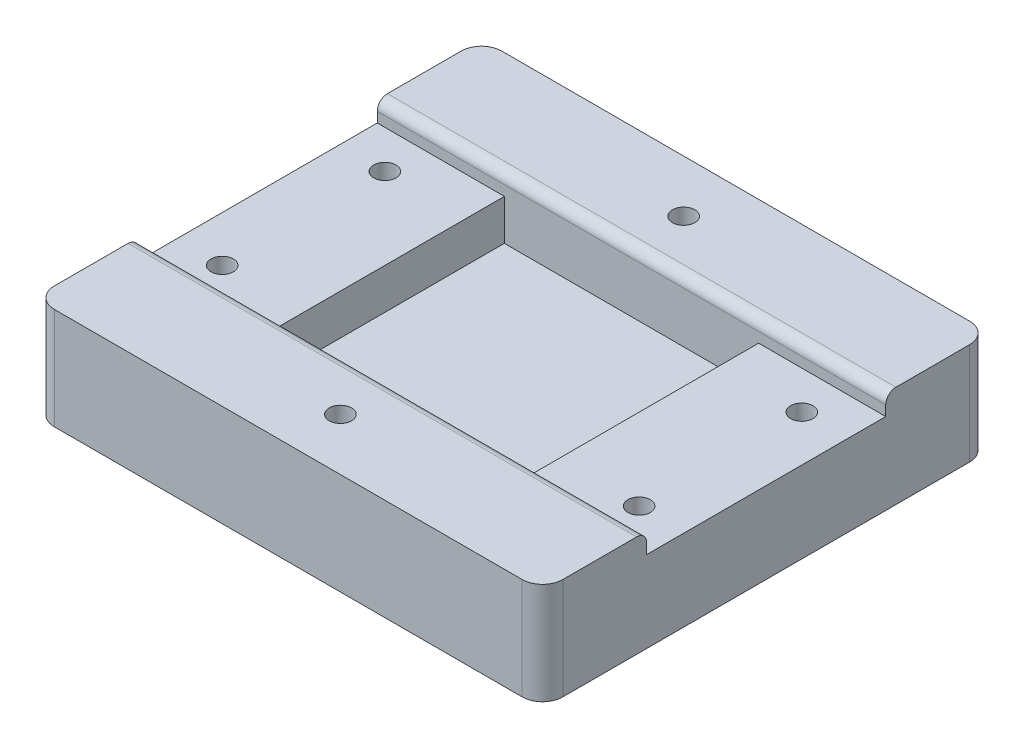
SolidWorks part; units mm, degrees
ref_plane "Alzado" through (0, 0, 0) normal (0, 0, 1) x (1, 0, 0)
ref_plane "Planta" through (0, 0, 0) normal (0, 1, 0) x (1, 0, 0)
ref_plane "Vista lateral" through (0, 0, 0) normal (1, 0, 0) x (0, 0, -1)
sketch "Croquis1" plane through (0, 0, 0) normal (0, 1, 0) x (1, 0, 0)
  line L1 (25, -22) -> (-25, -22)
  line L2 (25, -22) -> (25, 22)
  line L3 (25, 22) -> (-25, 22)
  line L4 (-25, -22) -> (-25, 22)
  line L5 (25, -22) -> (-25, 22) construction
  line L6 (25, 22) -> (-25, -22) construction
  point P0 (0, 0)
  dimension "D1" = 44
  dimension "D2" = 50
extrude "Saliente-Extruir1" add sketch "Croquis1" along normal blind 10
sketch "Croquis2" plane through (0, 10, 0) normal (0, 1, 0) x (1, 0, 0)
  line L1 (29, -11.75) -> (-29, -11.75)
  line L2 (29, -11.75) -> (29, 11.75)
  line L3 (29, 11.75) -> (-29, 11.75)
  line L4 (-29, -11.75) -> (-29, 11.75)
  line L5 (29, -11.75) -> (-29, 11.75) construction
  line L6 (29, 11.75) -> (-29, -11.75) construction
  point P0 (0, 0)
  dimension "D1" = 23.5
  dimension "D2" = 58
extrude "Cortar-Extruir2" cut sketch "Croquis2" against normal blind 2
sketch "Croquis3" plane through (0, 8, 0) normal (0, 1, 0) x (1, 0, 0)
  line L0 (25, 11.75) -> (-25, 11.75) construction
  line L1 (12.5, -11.75) -> (-12.5, -11.75)
  line L2 (12.5, -11.75) -> (12.5, 11.75)
  line L3 (12.5, 11.75) -> (-12.5, 11.75)
  line L4 (-12.5, -11.75) -> (-12.5, 11.75)
  line L5 (12.5, -11.75) -> (-12.5, 11.75) construction
  line L6 (12.5, 11.75) -> (-12.5, -11.75) construction
  point P0 (0, 0)
  dimension "D1" = 25
extrude "Cortar-Extruir3" cut sketch "Croquis3" against normal blind 4
sketch "Croquis4" plane through (0, 8, 0) normal (0, 1, 0) x (1, 0, 0)
  line L0 (-25, 8) -> (25, 8) construction
  line L1 (-25, 11.75) -> (-25, -11.75) construction
  line L2 (25, -11.75) -> (25, 11.75) construction
  line L3 (-25, -8) -> (25, -8) construction
  line L4 (-20.5, 11.75) -> (-20.5, -11.75) construction
  line L5 (-12.5, 11.75) -> (-25, 11.75) construction
  line L6 (-25, -11.75) -> (25, -11.75) construction
  line L7 (20.5, 11.75) -> (20.5, -11.75) construction
  line L8 (25, 11.75) -> (-25, 11.75) construction
  line L9 (-12.5, 11.75) -> (-12.5, -11.75) construction
  line L10 (12.5, -11.75) -> (12.5, 11.75) construction
  circle A0 centre (-20.5, 8) radius 1.1
  circle A1 centre (-20.5, -8) radius 1.1
  circle A2 centre (20.5, 8) radius 1.1
  circle A3 centre (20.5, -8) radius 1.1
  point P23 (-20.5, 8)
  point P24 (-20.5, -8)
  point P25 (20.5, -8)
  point P26 (20.5, 8)
  dimension "D5" = 2.2
  dimension "D6" = 2.2
  dimension "D7" = 2.2
  dimension "D8" = 2.2
  dimension "D1" = 8
  dimension "D2" = 8
  dimension "D3" = 8
  dimension "D4" = 8
extrude "Cortar-Extruir4" cut sketch "Croquis4" against normal blind 5
sketch "Croquis5" plane through (0, 10, 0) normal (0, 1, 0) x (1, 0, 0)
  line L0 (0, 22) -> (0, -22) construction
  line L1 (25, 22) -> (-25, 22) construction
  line L2 (-25, -22) -> (25, -22) construction
  line L3 (-25, 16.875) -> (25, 16.875) construction
  line L4 (-25, 22) -> (-25, 11.75) construction
  line L5 (25, 11.75) -> (25, 22) construction
  line L6 (-25, -16.875) -> (25, -16.875) construction
  line L7 (-25, -11.75) -> (-25, -22) construction
  line L8 (25, -22) -> (25, -11.75) construction
  circle A0 centre (0, 16.875) radius 1.1
  circle A1 centre (0, -16.875) radius 1.1
  point P18 (0, 16.875)
  point P19 (0, -16.875)
  dimension "D1" = 2.2
  dimension "D2" = 2.2
extrude "Cortar-Extruir5" cut sketch "Croquis5" against normal blind 5
fillet "Redondeo1" radius 2 4 edges at (-25, 5, -22) (-25, 5, 22) (25, 5, 22) (25, 5, -22)
fillet "Redondeo2" radius 1 2 edges at (0, 10, 11.75) (0, 10, -11.75)
